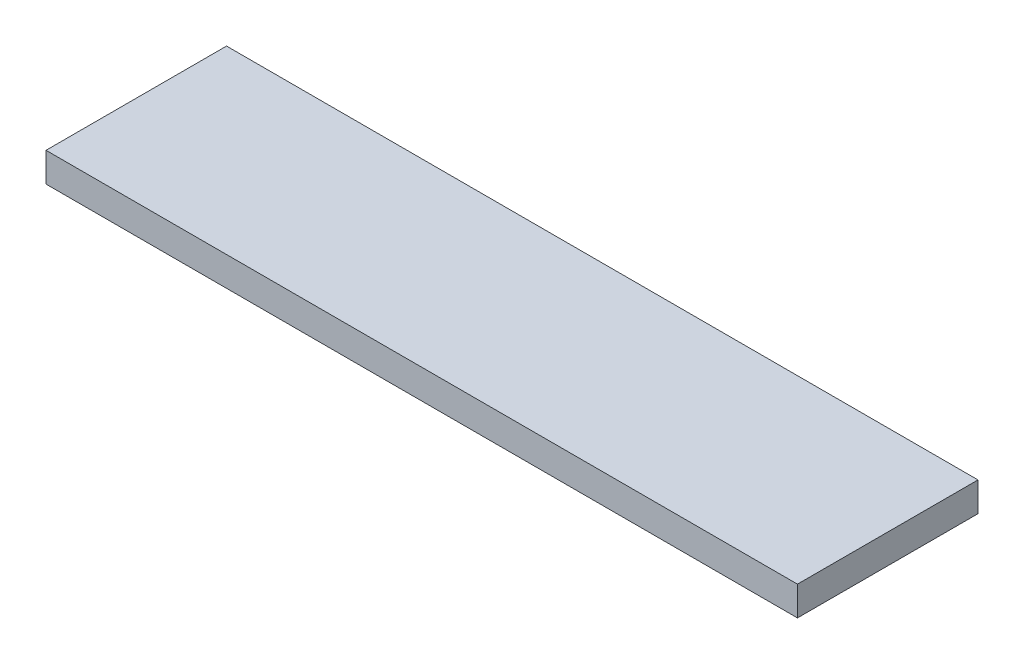
SolidWorks part; units mm, degrees
material "Pine"
ref_plane "Front Plane" through (0, 0, 0) normal (0, 0, 1) x (1, 0, 0)
ref_plane "Top Plane" through (0, 0, 0) normal (0, 1, 0) x (1, 0, 0)
ref_plane "Right Plane" through (0, 0, 0) normal (1, 0, 0) x (0, 0, -1)
sketch "Sketch1" plane through (0, 0, 0) normal (0, 1, 0) x (1, 0, 0)
  line L1 (-423.6906, 404.2151) -> (554.2094, 404.2151)
  line L2 (-423.6906, 404.2151) -> (-423.6906, 169.2651)
  line L3 (-423.6906, 169.2651) -> (554.2094, 169.2651)
  line L4 (554.2094, 404.2151) -> (554.2094, 169.2651)
  dimension "D1" = 977.9
  dimension "D2" = 234.95
extrude "Boss-Extrude1" add sketch "Sketch1" along normal blind 38.1 contours L1 L4 L3 L2
